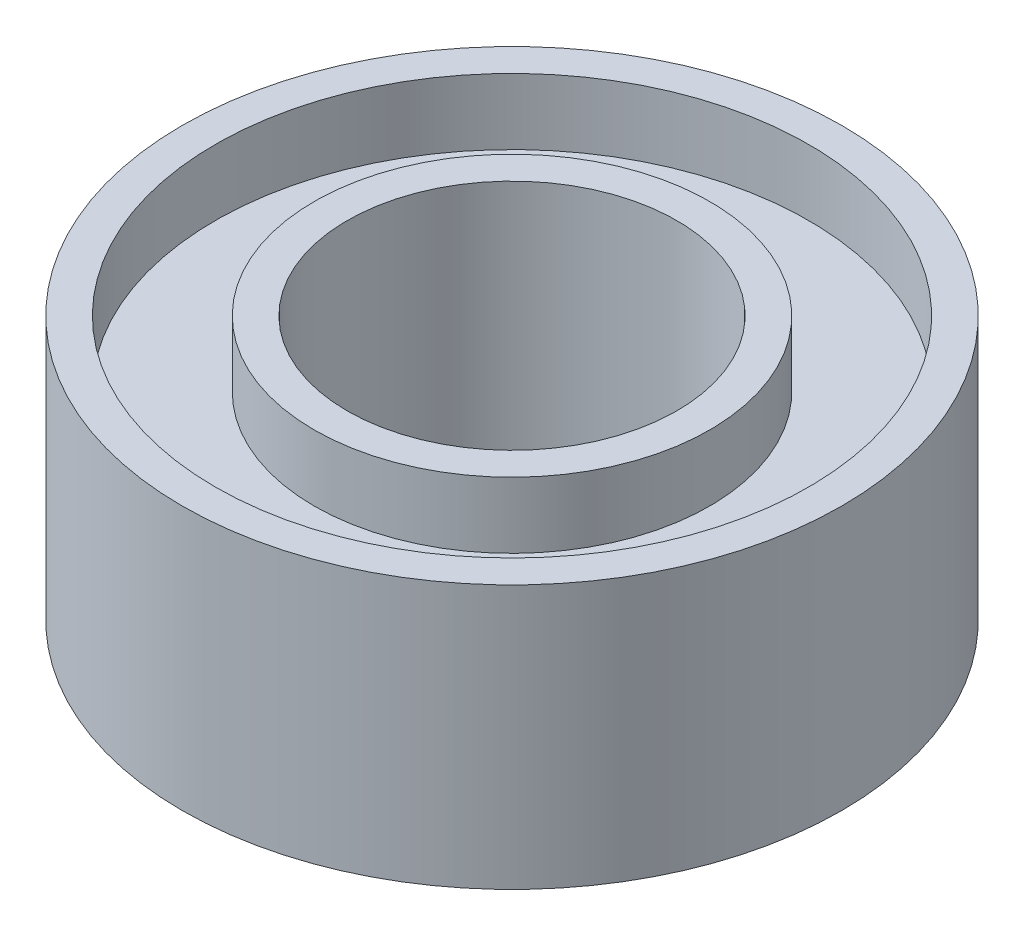
SolidWorks part; units mm, degrees
ref_plane "Front Plane" through (0, 0, 0) normal (0, 0, 1) x (1, 0, 0)
ref_plane "Top Plane" through (0, 0, 0) normal (0, 1, 0) x (1, 0, 0)
ref_plane "Right Plane" through (0, 0, 0) normal (1, 0, 0) x (0, 0, -1)
sketch "Sketch1" plane through (0, 0, 0) normal (0, 1, 0) x (1, 0, 0)
  circle A0 centre (0, 0) radius 2.5
  circle A1 centre (0, 0) radius 5
  dimension "D1" = 5
  dimension "D2" = 10
extrude "Boss-Extrude1" add sketch "Sketch1" along normal blind 4
sketch "Sketch2" plane through (0, 4, 0) normal (0, 1, 0) x (1, 0, 0)
  circle A0 centre (0, 0) radius 4.5
  circle A1 centre (0, 0) radius 3
  dimension "D1" = 9
  dimension "6" = 6
extrude "Cut-Extrude1" cut sketch "Sketch2" against normal blind 1 contours A0 | A1
sketch "Sketch3" plane through (0, 0, 0) normal (0, -1, 0) x (1, 0, 0)
  circle A0 centre (0, 0) radius 4.5
  circle A1 centre (0, 0) radius 3
  dimension "D1" = 9
  dimension "D2" = 6
extrude "Cut-Extrude2" cut sketch "Sketch3" against normal blind 1 contours A0 | A1
